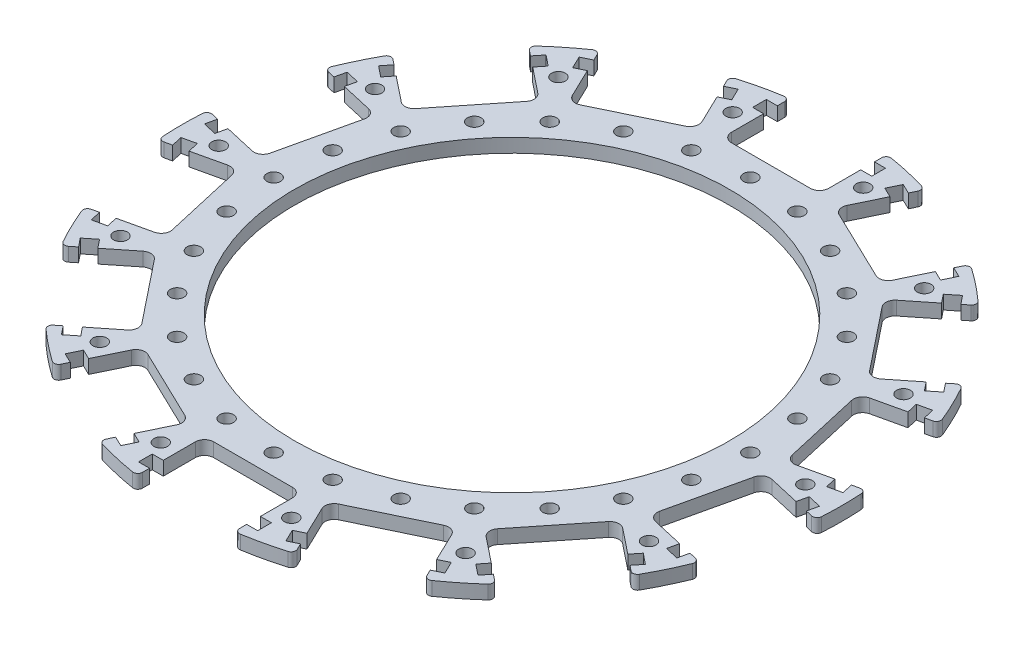
SolidWorks part; units mm, degrees
material "Thornel Mat VMA"
ref_plane "前视基准面" through (0, 0, 0) normal (0, 0, 1) x (1, 0, 0)
ref_plane "上视基准面" through (0, 0, 0) normal (0, 1, 0) x (1, 0, 0)
ref_plane "右视基准面" through (0, 0, 0) normal (1, 0, 0) x (0, 0, -1)
sketch "草图1" plane through (0, 0, 0) normal (0, 1, 0) x (1, 0, 0)
  line L0 (0, 0) -> (0, -67) construction
  line L1 (13, -67) -> (-13, -67) construction
  line L2 (-13, -68.5) -> (-13, -65.5)
  line L3 (0, -67) -> (0, -69.8577) construction
  line L4 (-10.1, -69.8577) -> (10.1, -69.8577) construction
  line L5 (-13, -68.5) -> (-10.6, -68.5)
  line L6 (-10.6, -68.5) -> (-10.6, -71.2154)
  line L7 (-13, -65.5) -> (-10.6, -65.5)
  line L8 (-10.6, -65.5) -> (-10.6, -56.5)
  line L9 (-10.6, -56.5) -> (10.6, -56.5)
  line L10 (10.6, -68.5) -> (10.6, -71.2154)
  line L11 (13, -68.5) -> (10.6, -68.5)
  line L12 (13, -68.5) -> (13, -65.5)
  line L13 (13, -65.5) -> (10.6, -65.5)
  line L14 (10.6, -65.5) -> (10.6, -56.5)
  line L15 (-34.0647, -46.3056) -> (-14.9642, -55.5039)
  line L16 (-37.9697, -54.4143) -> (-34.0647, -46.3056)
  line L17 (-40.132, -53.373) -> (-37.9697, -54.4143)
  line L18 (-41.4336, -56.0759) -> (-40.132, -53.373)
  line L19 (-41.4336, -56.0759) -> (-39.2713, -57.1172)
  line L20 (-39.2713, -57.1172) -> (-40.4495, -59.5637)
  line L21 (-20.1708, -66.3155) -> (-21.349, -68.7621)
  line L22 (-18.0084, -67.3569) -> (-20.1708, -66.3155)
  line L23 (-18.0084, -67.3569) -> (-16.7068, -64.6539)
  line L24 (-16.7068, -64.6539) -> (-18.8691, -63.6126)
  line L25 (-18.8691, -63.6126) -> (-14.9642, -55.5039)
  line L26 (-50.7825, -26.9398) -> (-37.5645, -43.5146)
  line L27 (-57.819, -32.5512) -> (-50.7825, -26.9398)
  line L28 (-59.3153, -30.6748) -> (-57.819, -32.5512)
  line L29 (-61.6608, -32.5452) -> (-59.3153, -30.6748)
  line L30 (-61.6608, -32.5452) -> (-60.1644, -34.4216)
  line L31 (-60.1644, -34.4216) -> (-62.2875, -36.1147)
  line L32 (-46.9465, -50.9965) -> (-49.0695, -52.6895)
  line L33 (-45.4501, -52.8729) -> (-46.9465, -50.9965)
  line L34 (-45.4501, -52.8729) -> (-43.1046, -51.0024)
  line L35 (-43.1046, -51.0024) -> (-44.601, -49.126)
  line L36 (-44.601, -49.126) -> (-37.5645, -43.5146)
  line L37 (-57.4421, -2.2382) -> (-52.7247, -22.9067)
  line L38 (-66.2165, -4.2409) -> (-57.4421, -2.2382)
  line L39 (-66.7506, -1.9011) -> (-66.2165, -4.2409)
  line L40 (-69.6753, -2.5686) -> (-66.7506, -1.9011)
  line L41 (-69.6753, -2.5686) -> (-69.1413, -4.9084)
  line L42 (-69.1413, -4.9084) -> (-71.7886, -5.5127)
  line L43 (-64.4238, -25.5769) -> (-67.0712, -26.1812)
  line L44 (-63.8898, -27.9167) -> (-64.4238, -25.5769)
  line L45 (-63.8898, -27.9167) -> (-60.965, -27.2492)
  line L46 (-60.965, -27.2492) -> (-61.4991, -24.9094)
  line L47 (-61.4991, -24.9094) -> (-52.7247, -22.9067)
  line L48 (-52.7247, 22.9067) -> (-57.4421, 2.2382)
  line L49 (-61.4991, 24.9094) -> (-52.7247, 22.9067)
  line L50 (-60.965, 27.2492) -> (-61.4991, 24.9094)
  line L51 (-63.8898, 27.9167) -> (-60.965, 27.2492)
  line L52 (-63.8898, 27.9167) -> (-64.4238, 25.5769)
  line L53 (-64.4238, 25.5769) -> (-67.0712, 26.1812)
  line L54 (-69.1413, 4.9084) -> (-71.7886, 5.5127)
  line L55 (-69.6753, 2.5686) -> (-69.1413, 4.9084)
  line L56 (-69.6753, 2.5686) -> (-66.7506, 1.9011)
  line L57 (-66.7506, 1.9011) -> (-66.2165, 4.2409)
  line L58 (-66.2165, 4.2409) -> (-57.4421, 2.2382)
  line L59 (-37.5645, 43.5146) -> (-50.7825, 26.9398)
  line L60 (-44.601, 49.126) -> (-37.5645, 43.5146)
  line L61 (-43.1046, 51.0024) -> (-44.601, 49.126)
  line L62 (-45.4501, 52.8729) -> (-43.1046, 51.0024)
  line L63 (-45.4501, 52.8729) -> (-46.9465, 50.9965)
  line L64 (-46.9465, 50.9965) -> (-49.0695, 52.6895)
  line L65 (-60.1644, 34.4216) -> (-62.2875, 36.1147)
  line L66 (-61.6608, 32.5452) -> (-60.1644, 34.4216)
  line L67 (-61.6608, 32.5452) -> (-59.3153, 30.6748)
  line L68 (-59.3153, 30.6748) -> (-57.819, 32.5512)
  line L69 (-57.819, 32.5512) -> (-50.7825, 26.9398)
  line L70 (-14.9642, 55.5039) -> (-34.0647, 46.3056)
  line L71 (-18.8691, 63.6126) -> (-14.9642, 55.5039)
  line L72 (-16.7068, 64.6539) -> (-18.8691, 63.6126)
  line L73 (-18.0084, 67.3569) -> (-16.7068, 64.6539)
  line L74 (-18.0084, 67.3569) -> (-20.1708, 66.3155)
  line L75 (-20.1708, 66.3155) -> (-21.349, 68.7621)
  line L76 (-39.2713, 57.1172) -> (-40.4495, 59.5637)
  line L77 (-41.4336, 56.0759) -> (-39.2713, 57.1172)
  line L78 (-41.4336, 56.0759) -> (-40.132, 53.373)
  line L79 (-40.132, 53.373) -> (-37.9697, 54.4143)
  line L80 (-37.9697, 54.4143) -> (-34.0647, 46.3056)
  line L81 (10.6, 56.5) -> (-10.6, 56.5)
  line L82 (10.6, 65.5) -> (10.6, 56.5)
  line L83 (13, 65.5) -> (10.6, 65.5)
  line L84 (13, 68.5) -> (13, 65.5)
  line L85 (13, 68.5) -> (10.6, 68.5)
  line L86 (10.6, 68.5) -> (10.6, 71.2154)
  line L87 (-10.6, 68.5) -> (-10.6, 71.2154)
  line L88 (-13, 68.5) -> (-10.6, 68.5)
  line L89 (-13, 68.5) -> (-13, 65.5)
  line L90 (-13, 65.5) -> (-10.6, 65.5)
  line L91 (-10.6, 65.5) -> (-10.6, 56.5)
  line L92 (34.0647, 46.3056) -> (14.9642, 55.5039)
  line L93 (37.9697, 54.4143) -> (34.0647, 46.3056)
  line L94 (40.132, 53.373) -> (37.9697, 54.4143)
  line L95 (41.4336, 56.0759) -> (40.132, 53.373)
  line L96 (41.4336, 56.0759) -> (39.2713, 57.1172)
  line L97 (39.2713, 57.1172) -> (40.4495, 59.5637)
  line L98 (20.1708, 66.3155) -> (21.349, 68.7621)
  line L99 (18.0084, 67.3569) -> (20.1708, 66.3155)
  line L100 (18.0084, 67.3569) -> (16.7068, 64.6539)
  line L101 (16.7068, 64.6539) -> (18.8691, 63.6126)
  line L102 (18.8691, 63.6126) -> (14.9642, 55.5039)
  line L103 (50.7825, 26.9398) -> (37.5645, 43.5146)
  line L104 (57.819, 32.5512) -> (50.7825, 26.9398)
  line L105 (59.3153, 30.6748) -> (57.819, 32.5512)
  line L106 (61.6608, 32.5452) -> (59.3153, 30.6748)
  line L107 (61.6608, 32.5452) -> (60.1644, 34.4216)
  line L108 (60.1644, 34.4216) -> (62.2875, 36.1147)
  line L109 (46.9465, 50.9965) -> (49.0695, 52.6895)
  line L110 (45.4501, 52.8729) -> (46.9465, 50.9965)
  line L111 (45.4501, 52.8729) -> (43.1046, 51.0024)
  line L112 (43.1046, 51.0024) -> (44.601, 49.126)
  line L113 (44.601, 49.126) -> (37.5645, 43.5146)
  line L114 (57.4421, 2.2382) -> (52.7247, 22.9067)
  line L115 (66.2165, 4.2409) -> (57.4421, 2.2382)
  line L116 (66.7506, 1.9011) -> (66.2165, 4.2409)
  line L117 (69.6753, 2.5686) -> (66.7506, 1.9011)
  line L118 (69.6753, 2.5686) -> (69.1413, 4.9084)
  line L119 (69.1413, 4.9084) -> (71.7886, 5.5127)
  line L120 (64.4238, 25.5769) -> (67.0712, 26.1812)
  line L121 (63.8898, 27.9167) -> (64.4238, 25.5769)
  line L122 (63.8898, 27.9167) -> (60.965, 27.2492)
  line L123 (60.965, 27.2492) -> (61.4991, 24.9094)
  line L124 (61.4991, 24.9094) -> (52.7247, 22.9067)
  line L125 (52.7247, -22.9067) -> (57.4421, -2.2382)
  line L126 (61.4991, -24.9094) -> (52.7247, -22.9067)
  line L127 (60.965, -27.2492) -> (61.4991, -24.9094)
  line L128 (63.8898, -27.9167) -> (60.965, -27.2492)
  line L129 (63.8898, -27.9167) -> (64.4238, -25.5769)
  line L130 (64.4238, -25.5769) -> (67.0712, -26.1812)
  line L131 (69.1413, -4.9084) -> (71.7886, -5.5127)
  line L132 (69.6753, -2.5686) -> (69.1413, -4.9084)
  line L133 (69.6753, -2.5686) -> (66.7506, -1.9011)
  line L134 (66.7506, -1.9011) -> (66.2165, -4.2409)
  line L135 (66.2165, -4.2409) -> (57.4421, -2.2382)
  line L136 (37.5645, -43.5146) -> (50.7825, -26.9398)
  line L137 (44.601, -49.126) -> (37.5645, -43.5146)
  line L138 (43.1046, -51.0024) -> (44.601, -49.126)
  line L139 (45.4501, -52.8729) -> (43.1046, -51.0024)
  line L140 (45.4501, -52.8729) -> (46.9465, -50.9965)
  line L141 (46.9465, -50.9965) -> (49.0695, -52.6895)
  line L142 (60.1644, -34.4216) -> (62.2875, -36.1147)
  line L143 (61.6608, -32.5452) -> (60.1644, -34.4216)
  line L144 (61.6608, -32.5452) -> (59.3153, -30.6748)
  line L145 (59.3153, -30.6748) -> (57.819, -32.5512)
  line L146 (57.819, -32.5512) -> (50.7825, -26.9398)
  line L147 (14.9642, -55.5039) -> (34.0647, -46.3056)
  line L148 (18.8691, -63.6126) -> (14.9642, -55.5039)
  line L149 (16.7068, -64.6539) -> (18.8691, -63.6126)
  line L150 (18.0084, -67.3569) -> (16.7068, -64.6539)
  line L151 (18.0084, -67.3569) -> (20.1708, -66.3155)
  line L152 (20.1708, -66.3155) -> (21.349, -68.7621)
  line L153 (39.2713, -57.1172) -> (40.4495, -59.5637)
  line L154 (41.4336, -56.0759) -> (39.2713, -57.1172)
  line L155 (41.4336, -56.0759) -> (40.132, -53.373)
  line L156 (40.132, -53.373) -> (37.9697, -54.4143)
  line L157 (37.9697, -54.4143) -> (34.0647, -46.3056)
  circle A0 centre (0, 0) radius 67 construction
  circle A1 centre (0, 0) radius 72
  point P7 (0, -67)
  point P10 (-13, -67)
  point P18 (10.6, -69.8577)
  point P21 (0, -69.8577)
  point P26 (0, -56.5)
  point P185 (0, 0)
  dimension "D1" = 134
  dimension "D5" = 144
  dimension "D2" = 26
  dimension "D3" = 3
  dimension "D4" = 20.2
  dimension "D6" = 0.5
  dimension "D7" = 10.5
  dimension "D8" = 14
extrude "凸台-拉伸1" add sketch "草图1" along normal blind 3 contours L10 A1 L152 L151 L150 L149 L148 L147 L157 L156 L155 L154 L153 L141 L140 L139 L138 L137 L136 L146 L145 L144 L143 L142 L130 L129 L128 L127 L126 L125 L135 L134 L133 L132 L131 L119 L118 L117 L116 L115 L114 L124 L123 L122 L121 L120 L108
fillet "圆角1" radius 2 28 edges at (50.7825, 1.5, 26.9398) (57.4421, 1.5, 2.2382) (52.7247, 1.5, -22.9067) (37.5645, 1.5, -43.5146) (14.9642, 1.5, -55.5039) (-10.6, 1.5, -56.5) (-34.0647, 1.5, -46.3056) (-50.7825, 1.5, -26.9398) (-57.4421, 1.5, -2.2382) (-52.7247, 1.5, 22.9067) (-37.5645, 1.5, 43.5146) (-14.9642, 1.5, 55.5039) (-34.0647, 1.5, 46.3056) (-50.7825, 1.5, 26.9398) (-57.4421, 1.5, 2.2382) (-52.7247, 1.5, -22.9067) (-37.5645, 1.5, -43.5146) (-14.9642, 1.5, -55.5039) (10.6, 1.5, -56.5) (34.0647, 1.5, -46.3056) (57.4421, 1.5, -2.2382) (50.7825, 1.5, -26.9398) (52.7247, 1.5, 22.9067) (37.5645, 1.5, 43.5146) (34.0647, 1.5, 46.3056) (14.9642, 1.5, 55.5039) (10.6, 1.5, 56.5) (-10.6, 1.5, 56.5)
fillet "圆角2" radius 1 28 edges at (40.4495, 1.5, 59.5637) (10.6, 1.5, 71.2154) (62.2875, 1.5, 36.1147) (71.7886, 1.5, 5.5127) (67.0712, 1.5, -26.1812) (49.0695, 1.5, -52.6895) (21.349, 1.5, -68.7621) (-10.6, 1.5, -71.2154) (-40.4495, 1.5, -59.5637) (-62.2875, 1.5, -36.1147) (-71.7886, 1.5, -5.5127) (-67.0712, 1.5, 26.1812) (-21.349, 1.5, 68.7621) (-49.0695, 1.5, 52.6895) (-40.4495, 1.5, 59.5637) (-62.2875, 1.5, 36.1147) (-71.7886, 1.5, 5.5127) (-67.0712, 1.5, -26.1812) (-49.0695, 1.5, -52.6895) (-21.349, 1.5, -68.7621) (10.6, 1.5, -71.2154) (40.4495, 1.5, -59.5637) (62.2875, 1.5, -36.1147) (71.7886, 1.5, -5.5127) (67.0712, 1.5, 26.1812) (49.0695, 1.5, 52.6895) (21.349, 1.5, 68.7621) (-10.6, 1.5, 71.2154)
sketch "草图2" plane through (0, 0, 0) normal (0, 1, 0) x (1, 0, 0)
  line L0 (64, 0) -> (0, 0) construction
  circle A0 centre (64, 0) radius 1.5
  circle A1 centre (57.662, -27.7686) radius 1.5
  circle A2 centre (39.9033, -50.0372) radius 1.5
  circle A3 centre (14.2413, -62.3954) radius 1.5
  circle A4 centre (-14.2413, -62.3954) radius 1.5
  circle A5 centre (-39.9033, -50.0372) radius 1.5
  circle A6 centre (-57.662, -27.7686) radius 1.5
  circle A7 centre (-64, 0) radius 1.5
  circle A8 centre (-57.662, 27.7686) radius 1.5
  circle A9 centre (-39.9033, 50.0372) radius 1.5
  circle A10 centre (-14.2413, 62.3954) radius 1.5
  circle A11 centre (14.2413, 62.3954) radius 1.5
  circle A12 centre (39.9033, 50.0372) radius 1.5
  circle A13 centre (57.662, 27.7686) radius 1.5
  point P32 (0, 0)
  dimension "D1" = 3
  dimension "D2" = 64
  dimension "D3" = 14
extrude "切除-拉伸1" cut sketch "草图2" along normal blind 11
sketch "草图3" plane through (0, 0, 0) normal (0, 1, 0) x (1, 0, 0)
  line L0 (0, -56.5) -> (0, -52.5) construction
  line L1 (-8.6, -56.5) -> (8.6, -56.5) construction
  circle A0 centre (0, 0) radius 9 construction
  circle A1 centre (0, 0) radius 28 construction
  circle A2 centre (0, 0) radius 52.5
  dimension "D1" = 18
  dimension "D2" = 56
  dimension "D3" = 4
extrude "切除-拉伸2" cut sketch "草图3" along normal blind 11 contours A0 | A2 A1
sketch "草图4" plane through (0, 3, 0) normal (0, 1, 0) x (1, 0, 0)
  circle A0 centre (0, 0) radius 47.5
  circle A1 centre (0, 0) radius 52.5
  dimension "D1" = 95
  dimension "D2" = 105
extrude "凸台-拉伸2" add sketch "草图4" against normal blind 3
sketch "草图5" plane through (0, 3, 0) normal (0, 1, 0) x (1, 0, 0)
  circle A0 centre (0, 0) radius 52 construction
  circle A1 centre (0, 52) radius 1.5
  circle A2 centre (11.5711, 50.6963) radius 1.5
  circle A3 centre (22.562, 46.8504) radius 1.5
  circle A4 centre (32.4215, 40.6552) radius 1.5
  circle A5 centre (40.6552, 32.4215) radius 1.5
  circle A6 centre (46.8504, 22.562) radius 1.5
  circle A7 centre (50.6963, 11.5711) radius 1.5
  circle A8 centre (52, 0) radius 1.5
  circle A9 centre (50.6963, -11.5711) radius 1.5
  circle A10 centre (46.8504, -22.562) radius 1.5
  circle A11 centre (40.6552, -32.4215) radius 1.5
  circle A12 centre (32.4215, -40.6552) radius 1.5
  circle A13 centre (22.562, -46.8504) radius 1.5
  circle A14 centre (11.5711, -50.6963) radius 1.5
  circle A15 centre (0, -52) radius 1.5
  circle A16 centre (-11.5711, -50.6963) radius 1.5
  circle A17 centre (-22.562, -46.8504) radius 1.5
  circle A18 centre (-32.4215, -40.6552) radius 1.5
  circle A19 centre (-40.6552, -32.4215) radius 1.5
  circle A20 centre (-46.8504, -22.562) radius 1.5
  circle A21 centre (-50.6963, -11.5711) radius 1.5
  circle A22 centre (-52, 0) radius 1.5
  circle A23 centre (-50.6963, 11.5711) radius 1.5
  circle A24 centre (-46.8504, 22.562) radius 1.5
  circle A25 centre (-40.6552, 32.4215) radius 1.5
  circle A26 centre (-32.4215, 40.6552) radius 1.5
  circle A27 centre (-22.562, 46.8504) radius 1.5
  circle A28 centre (-11.5711, 50.6963) radius 1.5
  point P61 (0, 0)
  dimension "D1" = 104
  dimension "D2" = 3
  dimension "D3" = 28
extrude "切除-拉伸3" cut sketch "草图5" against normal blind 3
